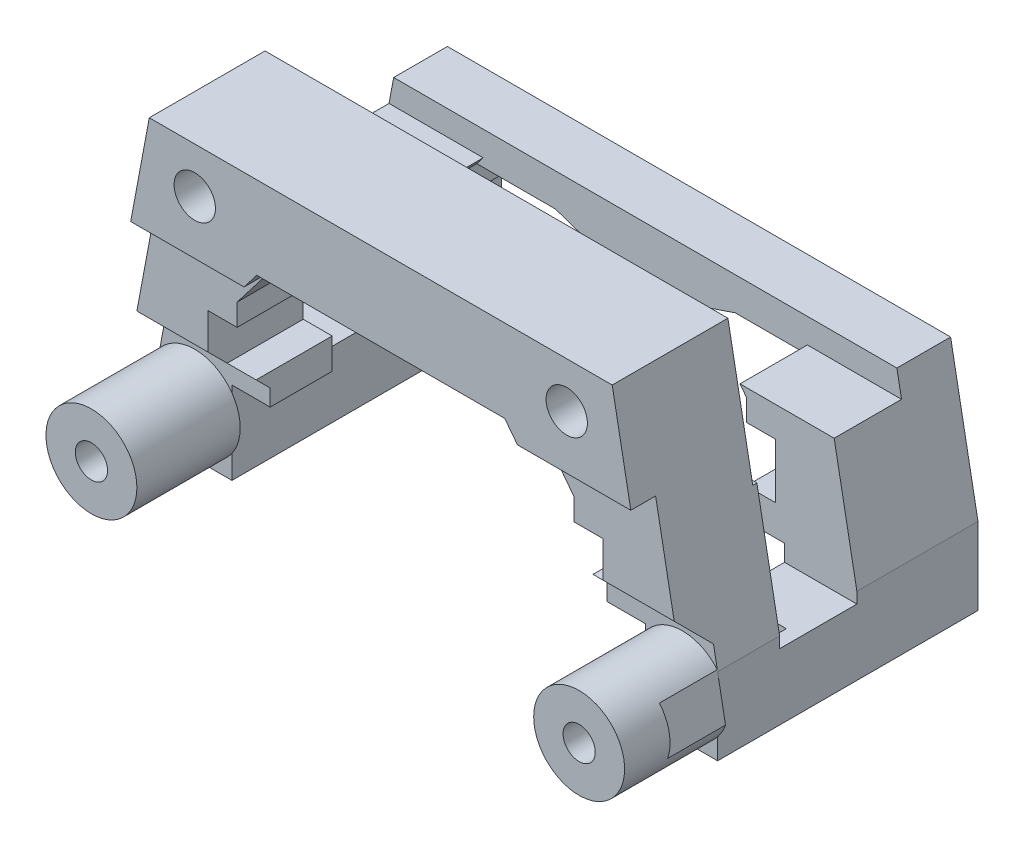
SolidWorks part; units mm, degrees
ref_plane "Front Plane" through (0, 0, 0) normal (0, 0, 1) x (1, 0, 0)
ref_plane "Top Plane" through (0, 0, 0) normal (0, 1, 0) x (1, 0, 0)
ref_plane "Right Plane" through (0, 0, 0) normal (1, 0, 0) x (0, 0, -1)
sketch "Szkic1" plane through (0, 0, 0) normal (1, 0, 0) x (0, 0, -1)
  line L0 (0, 54) -> (-13, 54)
  line L1 (0, 0) -> (-63, 0)
  line L2 (0, 0) -> (0, 54)
  line L3 (-49, 80) -> (-77, 80)
  line L4 (-77, 56) -> (-77, 80)
  line L5 (-13, 54) -> (-13, 48)
  line L6 (-13, 48) -> (-29.3, 48)
  line L7 (-29.3, 48) -> (-29.3, 16)
  line L8 (0, 0) -> (-63, 0)
  line L9 (-29.3, 16) -> (-49, 16)
  line L10 (-49, 16) -> (-49, 80)
  line L11 (-49, 80) -> (-77, 80)
  line L12 (-77, 80) -> (-77, 56)
  line L13 (-77, 56) -> (-71, 56)
  line L14 (-71, 56) -> (-71, 32)
  line L15 (-63, 0) -> (-63, 24)
  line L16 (-63, 24) -> (-71, 32)
  line L17 (-49, 48) -> (-48, 48)
  line L18 (-48, 48) -> (-48, 16)
  point P11 (-49, 16)
  point P17 (-49, 48)
  dimension "D1" = 54
  dimension "D2" = 80
  dimension "D3" = 29.3
  dimension "D4" = 6
  dimension "D5" = 23
  dimension "D6" = 16
  dimension "D8" = 28
  dimension "D9" = 22
  dimension "D10" = 19.7
  dimension "D11" = 13
  dimension "D12" = 32
  dimension "D13" = 24
  dimension "D14" = 48
  dimension "D15" = 24
  dimension "D16" = 15
extrude "Dodanie-wyciągnięcie1" add sketch "Szkic1" along normal mid plane 135 contours L16 L15 L1 L2 L0 L5 L6 L7 L9 L10 L3 L4 L13 L14 | L18 L17 L10 L9
sketch "Szkic2" plane through (0, 0, 0) normal (0, 0, -1) x (-1, 0, 0)
  line L1 (50, 0) -> (50, 20)
  line L2 (-50, 0) -> (50, 0)
  line L4 (-40.75, 46) -> (-21.75, 46)
  line L6 (50, 20) -> (40.75, 20)
  line L7 (40.75, 20) -> (40.75, 27.4)
  line L8 (40.75, 27.4) -> (47.75, 27.4)
  line L9 (47.75, 27.4) -> (47.75, 40.7)
  line L10 (47.75, 40.7) -> (40.75, 40.7)
  line L11 (40.75, 40.7) -> (40.75, 46)
  line L12 (0, 0) -> (0, 95.0692) construction
  line L13 (21.75, 46) -> (10, 42)
  line L14 (10, 42) -> (-10, 42)
  line L15 (-50, 0) -> (-50, 20)
  line L16 (-50, 20) -> (-40.75, 20)
  line L17 (-40.75, 20) -> (-40.75, 27.4)
  line L18 (-40.75, 27.4) -> (-47.75, 27.4)
  line L19 (-47.75, 27.4) -> (-47.75, 40.7)
  line L20 (-47.75, 40.7) -> (-40.75, 40.7)
  line L21 (-40.75, 40.7) -> (-40.75, 46)
  line L22 (-21.75, 46) -> (-10, 42)
  line L23 (21.75, 46) -> (40.75, 46)
  point P29 (0, 42)
  dimension "D4" = 46
  dimension "D2" = 20
  dimension "D3" = 100
  dimension "D5" = 27.4
  dimension "D6" = 13.3
  dimension "D7" = 42
  dimension "D8" = 26
  dimension "D9" = 10
  dimension "D10" = 95.5
  dimension "D11" = 7
  dimension "D12" = 7
extrude "Wytnij-wyciągnięcie1" cut sketch "Szkic2" against normal blind 94
sketch "Szkic4" plane through (0, 0, 49) normal (0, 0, -1) x (-1, 0, 0)
  line L0 (40.75, 40.7) -> (40.75, 46) construction
  line L5 (-40.75, 46) -> (-40.75, 40.7) construction
  line L6 (40.75, 40.7) -> (40.75, 46)
  line L8 (-40.75, 40.7) -> (40.75, 40.7)
  line L9 (40.75, 46) -> (30, 60)
  line L10 (30, 60) -> (-30, 60)
  line L11 (0, 60) -> (0, 40.7) construction
  line L12 (50, 0) -> (67.5, 0) construction
  line L14 (-30, 60) -> (-40.75, 46)
  line L15 (-40.75, 46) -> (-40.75, 40.7)
  dimension "D1" = 60
  dimension "D2" = 60
extrude "Wytnij-wyciągnięcie2" cut sketch "Szkic4" against normal blind 135 and the other way blind 36
sketch "Szkic6" plane through (0, 0, 77) normal (0, 0, 1) x (1, 0, 0)
  line L0 (67.5, 80) -> (-67.5, 80) construction
  line L3 (0, 17.6664) -> (0, 89.2176) construction
  circle A0 centre (-45, 69) radius 5
  circle A1 centre (45, 69) radius 5
  point P0 (-45, 69)
  dimension "D3" = 90
  dimension "D1" = 11
extrude "Wytnij-wyciągnięcie6" cut sketch "Szkic6" against normal up to next
sketch "Szkic7" plane through (0, 0, 63) normal (0, 0, 1) x (1, 0, 0)
  line L0 (-50, 0) -> (-67.5, 0) construction
  line L1 (-67.5, 0) -> (-67.5, 24) construction
  line L2 (0, 0) -> (0, 90.8003) construction
  circle A0 centre (-59, 12) radius 6.5
  circle A1 centre (59, 12) radius 6.5
  dimension "D1" = 12
  dimension "D2" = 8.5
  dimension "D3" = 118
extrude "Wytnij-wyciągnięcie7" cut sketch "Szkic7" against normal blind 20
sketch "Szkic8" plane through (0, 0, 63) normal (0, 0, 1) x (1, 0, 0)
  line L0 (0, 0) -> (0, 67.8224) construction
  circle A0 centre (-59, 12) radius 11
  circle A1 centre (-59, 12) radius 3.9
  circle A3 centre (59, 12) radius 11
  circle A4 centre (59, 12) radius 3.9
  dimension "D1" = 7.8
  dimension "D2" = 22
extrude "Dodanie-wyciągnięcie2" add sketch "Szkic8" along normal blind 25 contours A0
sketch "Szkic9" plane through (0, 0, 77) normal (0, 0, 1) x (1, 0, 0)
  line L0 (0, 0) -> (0, 80) construction
  line L1 (67.5, 80) -> (-67.5, 80) construction
  line L2 (-71, 0) -> (-56, 80)
  line L3 (-71, 0) -> (-104.1979, 0)
  line L4 (-104.1979, 0) -> (-104.1979, 108.6506)
  line L5 (-104.1979, 108.6506) -> (104.1979, 108.6506)
  line L6 (104.1979, 0) -> (104.1979, 108.6506)
  line L7 (71, 0) -> (104.1979, 0)
  line L8 (71, 0) -> (56, 80)
  line L9 (56, 80) -> (-56, 80)
  point P11 (0, 108.6506)
  dimension "D1" = 112
  dimension "D2" = 142
extrude "Wytnij-wyciągnięcie8" cut sketch "Szkic9" against normal blind 94
